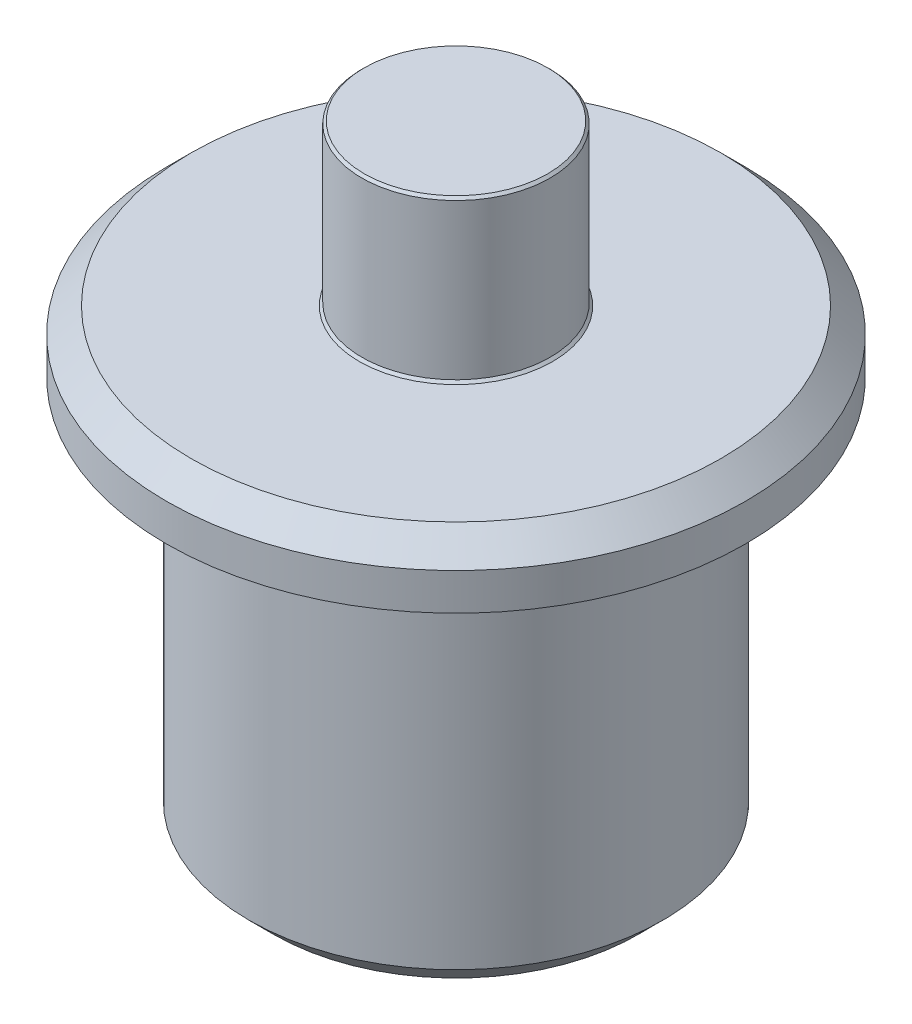
SolidWorks part; units mm, degrees
ref_plane "Спереди" through (0, 0, 0) normal (0, 0, 1) x (1, 0, 0)
ref_plane "Сверху" through (0, 0, 0) normal (0, 1, 0) x (1, 0, 0)
ref_plane "Справа" through (0, 0, 0) normal (1, 0, 0) x (0, 0, -1)
sketch "Эскиз1" plane through (0, 0, 0) normal (0, 1, 0) x (1, 0, 0)
  circle A0 centre (0, 0) radius 8.4
  dimension "D1" = 16.8
extrude "Бобышка-Вытянуть1" add sketch "Эскиз1" along normal blind 15.9
sketch "Эскиз2" plane through (0, 15.9, 0) normal (0, 1, 0) x (1, 0, 0)
  circle A0 centre (0, 0) radius 11.75
  dimension "D1" = 23.5
extrude "Бобышка-Вытянуть2" add sketch "Эскиз2" along normal blind 2.5
sketch "Эскиз3" plane through (0, 18.4, 0) normal (0, 1, 0) x (1, 0, 0)
  circle A0 centre (0, 0) radius 3.825
  dimension "D1" = 7.65
extrude "Бобышка-Вытянуть3" add sketch "Эскиз3" along normal blind 6.5
chamfer "Фаска1" distance 1 angle 45 2 edges at (0, 0, 8.4) (0, 18.4, 11.75)
chamfer "Фаска2" distance 0.1 angle 45 2 edges at (0, 24.9, 3.825) (0, 18.4, 3.825)
equation "\"big_bearing_d1\"= 19.9"
equation "\"big_bearing_d2\"= 42"
equation "\"big_bearing_h\"= 11.9"
equation "\"print_offset\"= 0.5"
equation "\"small_bearing_d1\"= 2.9"
equation "\"small_bearing_d2\"= 10"
equation "\"small_bearing_h\"= 4"
equation "\"tube_d\"= 16"
equation "\"small_bearing_distance\"= 2"
equation "\"D1@Эскиз1\"=16.8"
equation "\"D1@Бобышка-Вытянуть1\"=\"big_bearing_h\"+4"
equation "\"D1@Эскиз3\"=-\"print_offset\"/2+7.9"
